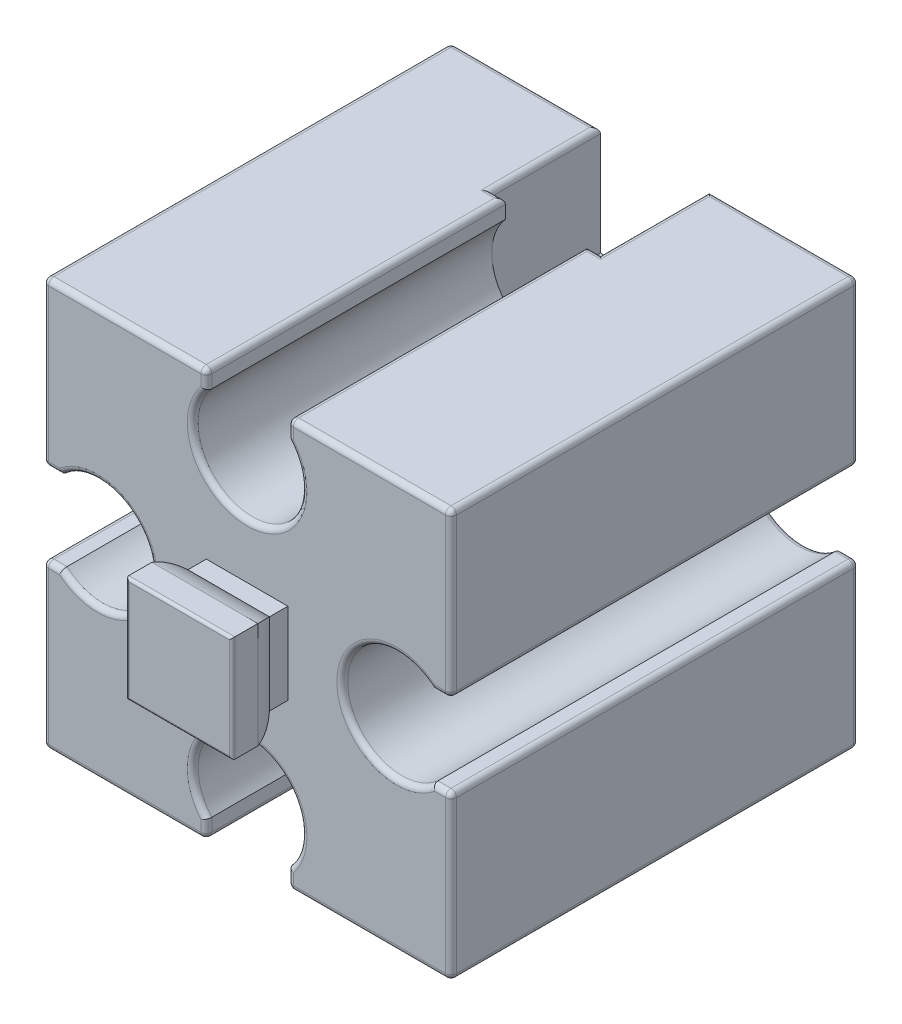
SolidWorks part; units mm, degrees
ref_plane "前视基准面" through (0, 0, 0) normal (0, 0, 1) x (1, 0, 0)
ref_plane "上视基准面" through (0, 0, 0) normal (0, 1, 0) x (1, 0, 0)
ref_plane "右视基准面" through (0, 0, 0) normal (1, 0, 0) x (0, 0, -1)
sketch "草图1" plane through (0, 0, 0) normal (0, 0, 1) x (1, 0, 0)
  line L1 (-7.5, -7.5) -> (7.5, -7.5)
  line L2 (-7.5, -7.5) -> (-7.5, 7.5)
  line L3 (-7.5, 7.5) -> (7.5, 7.5)
  line L4 (7.5, -7.5) -> (7.5, 7.5)
extrude "凸台-拉伸1" add sketch "草图1" against normal blind 15
sketch "草图2" plane through (0, 0, 0) normal (0, 1, 0) x (1, 0, 0)
  line L0 (-7.5, 0) -> (7.5, 0) construction
  line L1 (-1.5, 0) -> (1.5, 0)
  line L2 (-1.5, 0) -> (-1.5, -1)
  line L3 (-1.5, -1) -> (1.5, -1)
  line L4 (1.5, 0) -> (1.5, -1)
extrude "凸台-拉伸2" add sketch "草图2" along normal blind 1.5 and the other way blind 1.5
sketch "草图3" plane through (0, 0, 0) normal (0, 1, 0) x (1, 0, 0)
  line L1 (-1.95, -2.5) -> (1.95, -2.5)
  line L2 (-1.95, -2.5) -> (-1.95, -1.5556)
  line L3 (1.95, -2.5) -> (1.95, -1.5556)
  line L4 (-1.5, 0) -> (-1.5, -1) construction
  line L5 (-1.5, -0.6771) -> (1.5, -0.6771)
  arc A0 (-1.5, -0.6771) -> (-1.95, -1.5556) centre (0, -2) ccw
  arc A1 (1.95, -1.5556) -> (1.5, -0.6771) centre (0, -2) ccw
extrude "凸台-拉伸3" add sketch "草图3" along normal blind 3 and the other way blind 3
sketch "草图5" plane through (0, 0, 0) normal (0, 0, 1) x (1, 0, 0)
  line L0 (-7.5, -7.5) -> (7.5, -7.5) construction
  line L1 (-1.5, -7.5) -> (1.5, -7.5)
  line L2 (-1.5, -7.5) -> (-1.5, -6.8229)
  line L3 (-7.5, 7.5) -> (-7.5, -7.5) construction
  line L4 (1.5, -7.5) -> (1.5, -6.8229)
  line L6 (1.5, 7.5) -> (1.5, 6.8229)
  line L7 (-1.5, 7.5) -> (-1.5, 6.8229)
  line L8 (-1.5, 7.5) -> (1.5, 7.5)
  line L9 (-7.5, 1.5) -> (-6.8229, 1.5)
  line L10 (-7.5, 1.5) -> (-7.5, -1.5)
  line L11 (-7.5, -1.5) -> (-6.8229, -1.5)
  line L12 (7.5, -1.5) -> (6.8229, -1.5)
  line L13 (7.5, 1.5) -> (7.5, -1.5)
  line L14 (7.5, 1.5) -> (6.8229, 1.5)
  arc A0 (1.5, -6.8229) -> (-1.5, -6.8229) centre (0, -5.5) ccw
  arc A1 (1.5, 6.8229) -> (-1.5, 6.8229) centre (0, 5.5) cw
  arc A2 (-6.8229, -1.5) -> (-6.8229, 1.5) centre (-5.5, 0) ccw
  arc A3 (6.8229, -1.5) -> (6.8229, 1.5) centre (5.5, 0) cw
extrude "切除-拉伸2" cut sketch "草图5" against normal through all
sketch "草图6" plane through (0, 7.5, 0) normal (0, 1, 0) x (-1, 0, 0)
  line L0 (1.5, -15) -> (7.5, -15) construction
  line L1 (2, -15) -> (-2, -15)
  line L2 (2, -15) -> (2, -11)
  line L3 (2, -11) -> (-2, -11)
  line L4 (-2, -15) -> (-2, -11)
extrude "切除-拉伸3" cut sketch "草图6" against normal blind 4
sketch "草图9" plane through (0, -7.5, 0) normal (0, -1, 0) x (1, 0, 0)
  line L0 (-7.5, -15) -> (-1.5, -15) construction
  line L1 (-2, -15) -> (2, -15)
  line L2 (-2, -15) -> (-2, -11)
  line L3 (-2, -11) -> (2, -11)
  line L4 (2, -15) -> (2, -11)
extrude "切除-拉伸5" cut sketch "草图9" against normal blind 4
sketch "草图11" plane through (0, 0, 0) normal (0, 1, 0) x (1, 0, 0)
  line L0 (2, 15) -> (-2, 15) construction
  line L1 (-1.5, 15) -> (1.5, 15)
  line L2 (-1.5, 15) -> (-1.5, 14.3229)
  line L4 (1.5, 15) -> (1.5, 14.3229)
  arc A0 (-1.5, 14.3229) -> (1.5, 14.3229) centre (0, 13) ccw
extrude "切除-拉伸6" cut sketch "草图11" against normal through all and the other way through all
sketch "草图12" plane through (0, 0, 0) normal (1, 0, 0) x (0, 0, -1)
  line L0 (-2.5, 3) -> (-2.5, 1.95)
  line L1 (-2.5, 1.95) -> (-1.5556, 1.95)
  line L2 (-2.5, -1.95) -> (-1.5556, -1.95)
  line L5 (-2.5, -1.95) -> (-2.5, -3)
  line L6 (-2.5, 3) -> (-0.6771, 3)
  line L7 (-0.6771, 3) -> (-0.6771, 1.5)
  line L8 (-2.5, -3) -> (-0.6771, -3)
  line L9 (-0.6771, -3) -> (-0.6771, -1.5)
  arc A0 (-0.6771, 1.5) -> (-1.5556, 1.95) centre (-2, 0) ccw
  arc A1 (-1.5556, -1.95) -> (-0.6771, -1.5) centre (-2, 0) ccw
extrude "切除-拉伸7" cut sketch "草图12" against normal up to next and the other way up to next
fillet "圆角2" radius 0.1 4 edges at (-1.95, 0, 2.5) (0, -1.95, 2.5) (1.95, 0, 2.5) (0, 1.95, 2.5)
fillet "圆角3" radius 0.2 53 edges at (-4.75, 7.5, -15) (-7.5, 4.5, -15) (-7.1614, 1.5, -15) (-7.1614, -1.5, -15) (-7.5, -4.5, -15) (-4.75, -7.5, -15) (4.75, -7.5, -15) (7.5, -4.5, -15) (7.1614, -1.5, -15) (3.5, 0, -15) (7.1614, 1.5, -15) (7.5, 4.5, -15) (4.75, 7.5, -15) (7.1614, -1.5, 0) (7.5, -4.5, 0) (4.5, -7.5, 0) (1.5, -7.1614, 0) (0, -3.5, 0) (-1.5, -7.1614, 0) (-4.5, -7.5, 0) (-7.5, -4.5, 0) (-7.1614, -1.5, 0) (-3.5, 0, 0) (-7.1614, 1.5, 0) (-7.5, 4.5, 0) (-4.5, 7.5, 0) (-1.5, 7.1614, 0) (0, 3.5, 0) (1.5, 7.1614, 0) (4.5, 7.5, 0) (7.5, 4.5, 0) (7.1614, 1.5, 0) (3.5, 0, 0) (-7.5, -7.5, -7.5) (-1.5, -7.5, -5.5) (-1.75, -7.5, -11) (-2, -7.5, -13) (1.5, -7.5, -5.5) (7.5, -7.5, -7.5) (2, -7.5, -13) (1.75, -7.5, -11) (7.5, 7.5, -7.5) (1.5, 7.5, -5.5) (1.75, 7.5, -11) (2, 7.5, -13) (-1.75, 7.5, -11) (-1.5, 7.5, -5.5) (-7.5, 7.5, -7.5) (-2, 7.5, -13) (-7.5, 1.5, -7.5) (-7.5, -1.5, -7.5) (7.5, -1.5, -7.5) (7.5, 1.5, -7.5)
